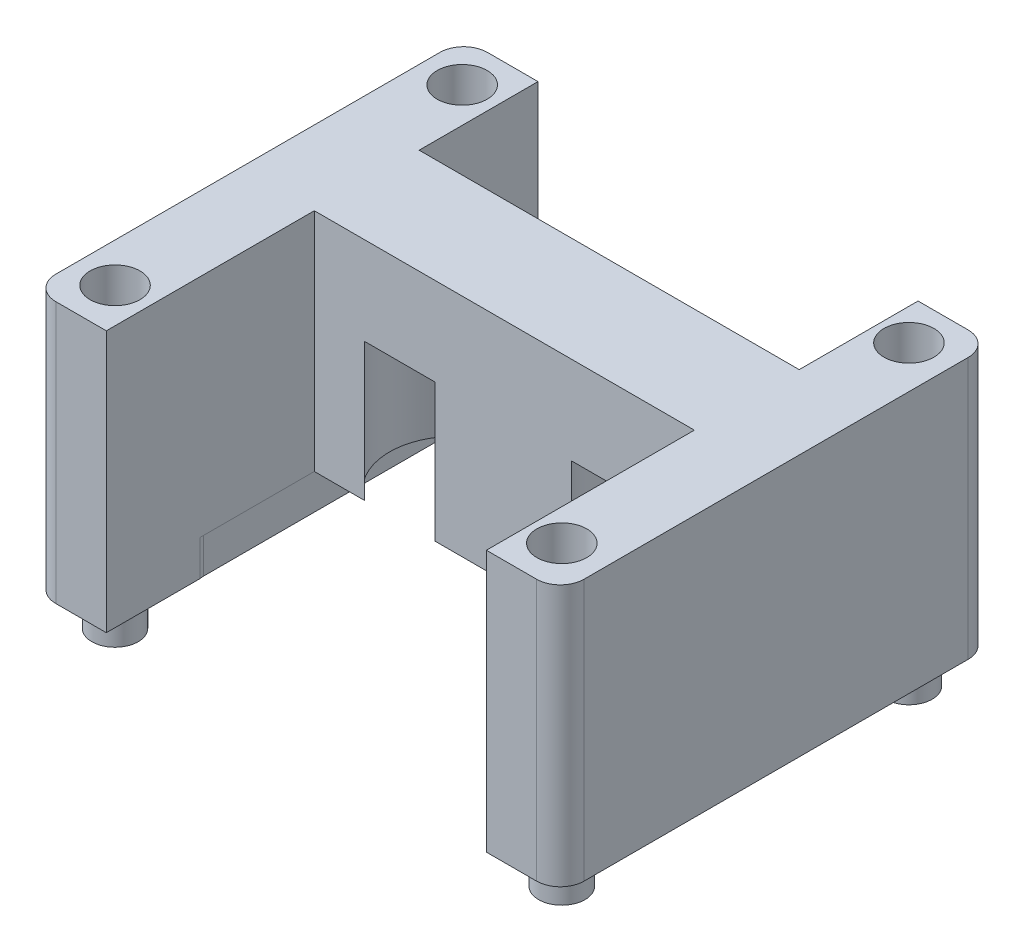
SolidWorks part; units mm, degrees
ref_plane "Спереди" through (0, 0, 0) normal (0, 0, 1) x (1, 0, 0)
ref_plane "Сверху" through (0, 0, 0) normal (0, 1, 0) x (1, 0, 0)
ref_plane "Справа" through (0, 0, 0) normal (1, 0, 0) x (0, 0, -1)
sketch "Эскиз1" plane through (0, 0, 0) normal (0, 1, 0) x (1, 0, 0)
  line L0 (0, 36.32) -> (44.45, 36.32)
  line L1 (0, 0) -> (44.45, 0)
  line L2 (44.45, 36.32) -> (44.45, 0)
  line L3 (0, 36.32) -> (0, 0)
  dimension "D1" = 44.45
  dimension "D2" = 36.32
extrude "Бобышка-Вытянуть1" add sketch "Эскиз1" along normal blind 22
sketch "Эскиз2" plane through (0, 22, 0) normal (0, 1, 0) x (1, 0, 0)
  line L0 (0, 36.32) -> (0, 0) construction
  line L1 (44.45, 36.32) -> (0, 36.32) construction
  line L2 (44.45, 0) -> (44.45, 36.32) construction
  line L3 (0, 0) -> (44.45, 0) construction
  circle A0 centre (3.302, 32.891) radius 2.1
  circle A1 centre (40.894, 32.89) radius 2.1
  circle A2 centre (40.894, 3.683) radius 2.1
  circle A3 centre (3.302, 3.683) radius 2.1
  circle A4 centre (22.225, 36.32) radius 1
  dimension "D1" = 4.2
  dimension "D4" = 4.2
  dimension "D5" = 4.2
  dimension "D6" = 4.2
  dimension "D13" = 2
  dimension "D2" = 3.302
  dimension "D3" = 3.429
  dimension "D7" = 3.43
  dimension "D8" = 3.556
  dimension "D9" = 3.556
  dimension "D10" = 3.683
  dimension "D11" = 3.302
  dimension "D12" = 3.683
extrude "Вырез-Вытянуть1" cut sketch "Эскиз2" against normal blind 3
fillet "Скругление2" radius 2 4 edges at (0, 11, -36.32) (44.45, 11, -36.32) (44.45, 11, 0) (0, 11, 0)
sketch "Эскиз5" plane through (0, 0, 0) normal (0, -1, 0) x (1, 0, 0)
  line L0 (0, -34.32) -> (0, -2) construction
  line L1 (6.22, -30.1) -> (38.23, -30.1)
  line L2 (6.22, -30.1) -> (6.22, -6.22)
  line L3 (6.22, -6.22) -> (38.23, -6.22)
  line L4 (38.23, -30.1) -> (38.23, -6.22)
  line L5 (44.45, -2) -> (44.45, -34.32) construction
  line L6 (2, 0) -> (42.45, 0) construction
  line L7 (42.45, -36.32) -> (2, -36.32) construction
  point P6 (0, -18.16)
  dimension "D1" = 6.22
  dimension "D2" = 6.22
  dimension "D3" = 6.22
  dimension "D4" = 6.22
extrude "Вырез-Вытянуть2" cut sketch "Эскиз5" against normal blind 3
fillet "Скругление3" radius 2 4 edges at (38.23, 1.5, -30.1) (6.22, 1.5, -30.1) (6.22, 1.5, -6.22) (38.23, 1.5, -6.22)
sketch "Эскиз6" plane through (0, 3, 0) normal (0, -1, 0) x (1, 0, 0)
  line L0 (44.45, -2) -> (44.45, -34.32) construction
  line L2 (0, -34.32) -> (0, -2) construction
  line L3 (42.45, -36.32) -> (2, -36.32) construction
  line L4 (42.45, -36.32) -> (2, -36.32) construction
  circle A0 centre (30.87, -22.09) radius 5.461
  circle A1 centre (13.45, -22.09) radius 5.461
  dimension "D1" = 10.922
  dimension "D4" = 10.922
  dimension "D2" = 13.58
  dimension "D3" = 14.23
  dimension "D5" = 13.45
  dimension "D6" = 14.23
extrude "Вырез-Вытянуть3" cut sketch "Эскиз6" against normal blind 11.5942
sketch "Эскиз7" plane through (0, 0, 0) normal (0, -1, 0) x (1, 0, 0)
  circle A0 centre (3.302, -3.683) radius 1.95
  circle A1 centre (3.302, -32.891) radius 1.95
  circle A2 centre (40.894, -32.89) radius 1.95
  circle A3 centre (40.894, -3.683) radius 1.95
  dimension "D1" = 3.9
  dimension "D2" = 3.9
  dimension "D3" = 3.9
  dimension "D4" = 3.9
extrude "Бобышка-Вытянуть2" add sketch "Эскиз7" along normal blind 3 separate body
sketch "Эскиз8" plane through (0, 0, 0) normal (0, -1, 0) x (1, 0, 0)
  line L5 (38.23, -28.1) -> (38.23, -8.22) construction
  line L6 (2, 0) -> (42.45, 0) construction
  line L7 (6.2524, 0) -> (38.23, 0)
  line L8 (6.2524, 0) -> (6.2524, -17.5)
  line L9 (6.2524, -17.5) -> (38.23, -17.5)
  line L10 (38.23, 0) -> (38.23, -17.5)
  line L11 (42.45, -36.32) -> (2, -36.32) construction
  line L12 (6.2524, -36.32) -> (38.23, -36.32)
  line L13 (6.2524, -36.32) -> (6.2524, -26.32)
  line L14 (6.2524, -26.32) -> (38.23, -26.32)
  line L15 (38.23, -36.32) -> (38.23, -26.32)
  line L16 (38.23, -28.1) -> (38.23, -8.22) construction
  dimension "D1" = 10
  dimension "D2" = 17.5
  dimension "D3" = 31.9776
  dimension "D4" = 31.9776
extrude "Вырез-Вытянуть4" cut sketch "Эскиз8" against normal through all
